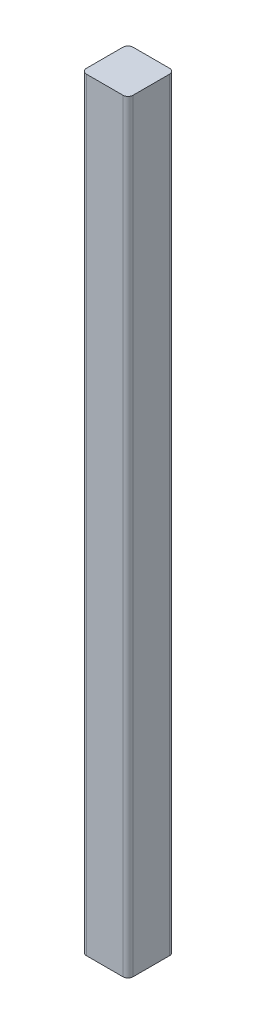
SolidWorks part; units mm, degrees
material "Plain Carbon Steel"
ref_plane "Front Plane" through (0, 0, 0) normal (0, 0, 1) x (1, 0, 0)
ref_plane "Top Plane" through (0, 0, 0) normal (0, 1, 0) x (1, 0, 0)
ref_plane "Right Plane" through (0, 0, 0) normal (1, 0, 0) x (0, 0, -1)
sketch "Sketch1" plane through (0, 0, 0) normal (0, 1, 0) x (1, 0, 0)
  line L1 (2.8, 0) -> (22.8, 0)
  line L2 (0, -2.8) -> (0, -22.8)
  line L3 (2.8, -25.6) -> (22.8, -25.6)
  line L4 (25.6, -2.8) -> (25.6, -22.8)
  arc A0 (22.8, 0) -> (25.6, -2.8) centre (22.8, -2.8) cw
  arc A1 (22.8, -25.6) -> (25.6, -22.8) centre (22.8, -22.8) ccw
  arc A2 (0, -22.8) -> (2.8, -25.6) centre (2.8, -22.8) ccw
  arc A3 (2.8, 0) -> (0, -2.8) centre (2.8, -2.8) ccw
  point P7 (25.6, 0)
  point P10 (25.6, -25.6)
  point P15 (0, 0)
  dimension "D2" = 2.8
  dimension "D1" = 25.6
extrude "Boss-Extrude1" add sketch "Sketch1" along normal blind 419.01
sketch "Sketch3" plane through (0, 0, 0) normal (0, -1, 0) x (-1, 0, 0)
  line L4 (-2.8, -2.8) -> (-22.8, -2.8)
  line L5 (-2.8, -2.8) -> (-2.8, -22.8)
  line L6 (-2.8, -22.8) -> (-22.8, -22.8)
  line L7 (-22.8, -2.8) -> (-22.8, -22.8)
  line L8 (-2.8, -2.8) -> (-22.8, -22.8) construction
  line L9 (-2.8, -22.8) -> (-22.8, -2.8) construction
  point P6 (-12.8, -12.8)
extrude "Cut-Extrude1" cut sketch "Sketch3" against normal blind 408.5
